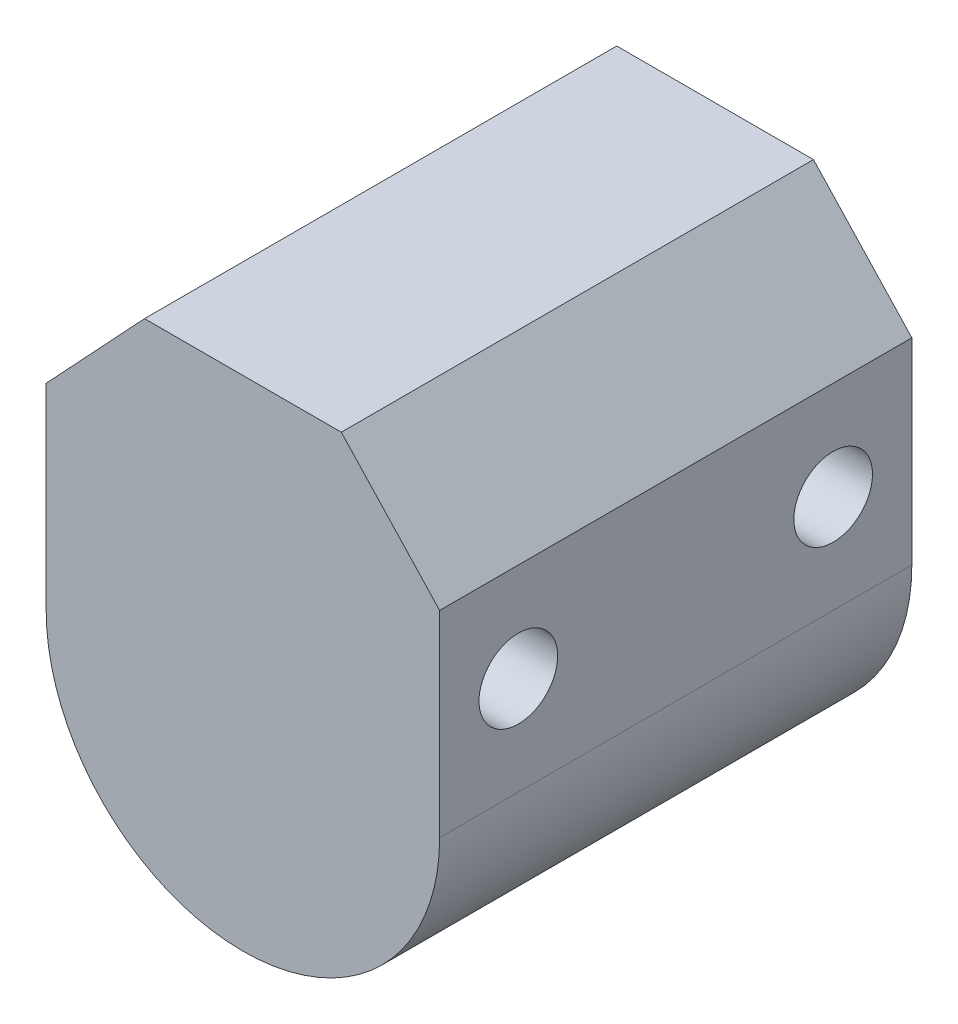
SolidWorks part; units mm, degrees
ref_plane "前视基准面" through (0, 0, 0) normal (0, 0, 1) x (1, 0, 0)
ref_plane "上视基准面" through (0, 0, 0) normal (0, 1, 0) x (1, 0, 0)
ref_plane "右视基准面" through (0, 0, 0) normal (1, 0, 0) x (0, 0, -1)
other "Configuration Table"
sketch "草图1" plane through (0, 0, 0) normal (0, 0, 1) x (1, 0, 0)
  line L0 (0, 0) -> (0, 10)
  line L1 (0, 10) -> (5, 15.3444)
  line L2 (5, 15.3444) -> (15, 15.3444)
  line L3 (15, 15.3444) -> (20, 10)
  line L4 (20, 10) -> (20, 0)
  line L5 (20, 0) -> (0, 0)
  line L6 (10, 15.3444) -> (10, 0)
  circle A0 centre (10, 0) radius 10
  dimension "D1" = 10
  dimension "D2" = 20
  dimension "D3" = 10
extrude "凸台-拉伸3" add sketch "草图1" along normal blind 24 contours A0 L6 L2 L1 L0 | A0 L4 L3 L2 L6 | L6 A0 L5 | L5 A0 L6 | L5 A0
sketch "草图4" plane through (20, 0, 0) normal (1, 0, 0) x (0, 0, -1)
  line L0 (-24, 10) -> (-12, 10)
  line L1 (-24, 10) -> (0, 10) construction
  line L2 (-12, 10) -> (-12, 0)
  line L3 (-24, 0) -> (0, 0) construction
  line L4 (-12, 0) -> (-12, 5)
  line L5 (-12, 5) -> (-20, 5)
  circle A0 centre (-20, 5) radius 2
  circle A1 centre (-4, 5) radius 2
  dimension "D2" = 4
  dimension "D1" = 8
extrude "切除-拉伸1" cut sketch "草图4" against normal through all both and the other way through all
